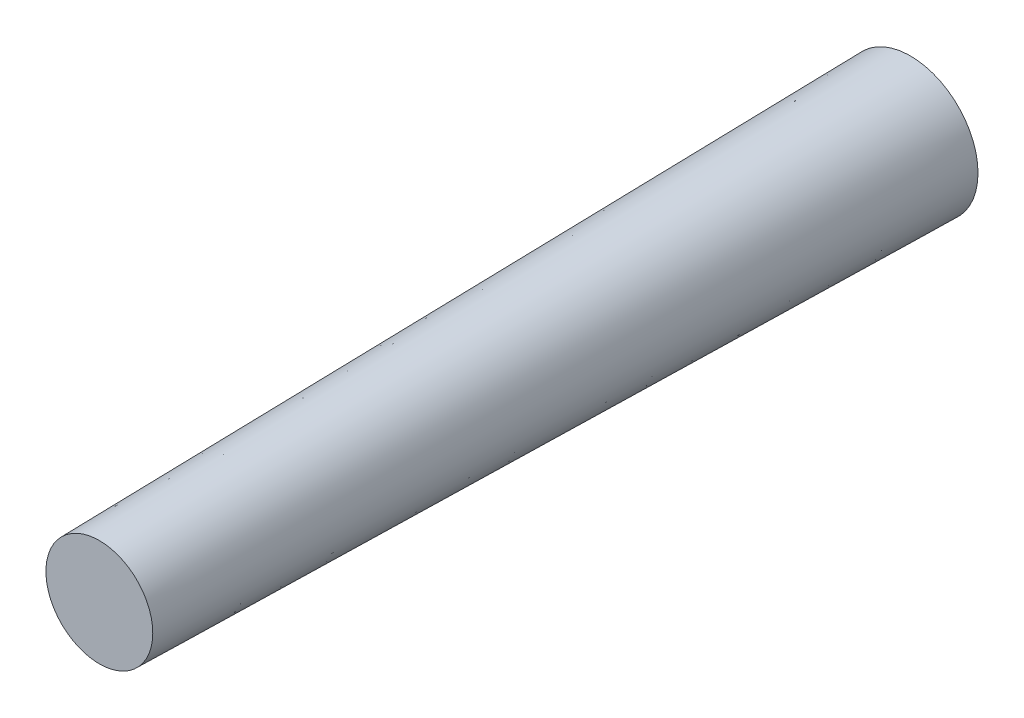
SolidWorks part; units mm, degrees
ref_plane "Front Plane" through (0, 0, 0) normal (0, 0, 1) x (1, 0, 0)
ref_plane "Top Plane" through (0, 0, 0) normal (0, 1, 0) x (1, 0, 0)
ref_plane "Right Plane" through (0, 0, 0) normal (1, 0, 0) x (0, 0, -1)
sketch "Sketch1" plane through (0, 0, 0) normal (0, 0, 1) x (1, 0, 0)
  circle A0 centre (0, 0) radius 2.5
  dimension "D1" = 5
extrude "Boss-Extrude1" add sketch "Sketch1" along normal blind 30
draft "Draft2" type of draft neutral plane draft angle 1 faces to draft 1 face at (2.5, 0, 30) neutral plane through (0, 0, 0) neutral plane normal (0, 0, -1) parameters "D1"=1
draft "Draft4" type of draft neutral plane draft angle 1 faces to draft 1 face at (3.0237, 0, 30) neutral plane through (0, 0, 0) neutral plane normal (0, 0, -1) reverse direction yes parameters "D1"=1
